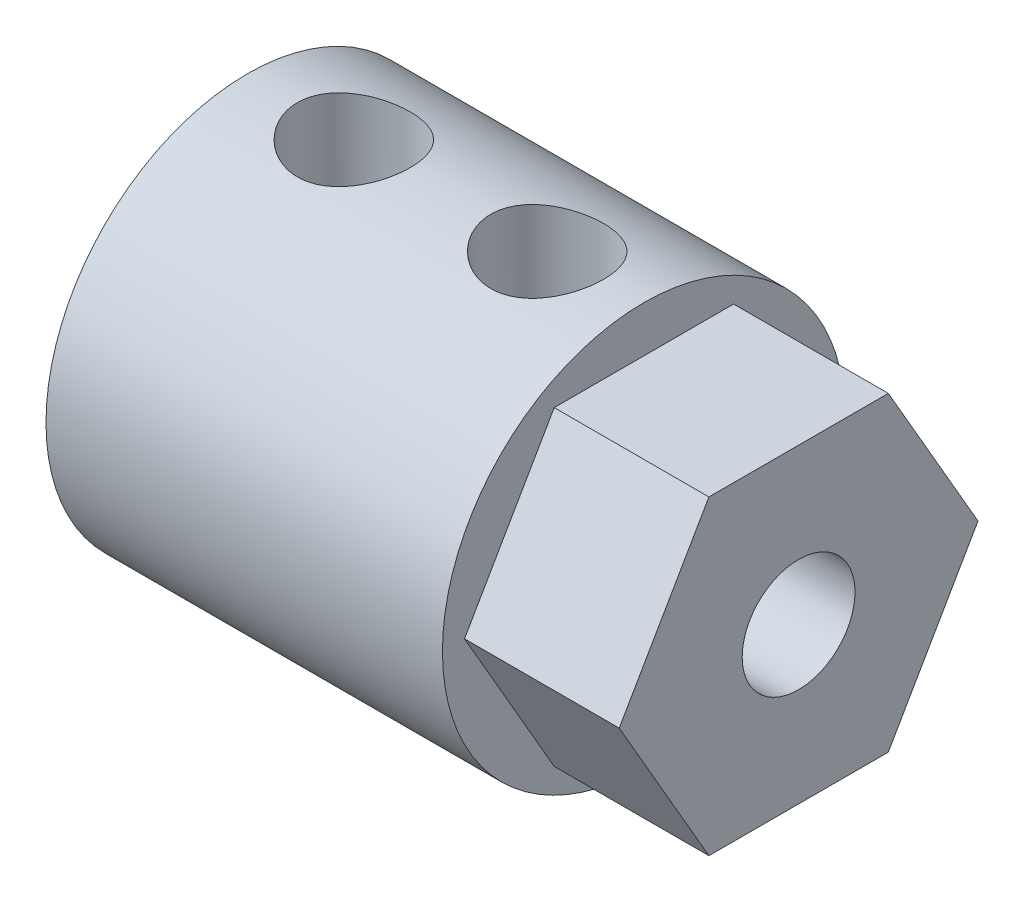
SolidWorks part; units mm, degrees
material "PLA2"
ref_plane "Front Plane" through (0, 0, 0) normal (0, 0, 1) x (1, 0, 0)
ref_plane "Top Plane" through (0, 0, 0) normal (0, 1, 0) x (1, 0, 0)
ref_plane "Right Plane" through (0, 0, 0) normal (1, 0, 0) x (0, 0, -1)
sketch "Sketch1" plane through (0, 0, 0) normal (1, 0, 0) x (0, 0, -1)
  line L0 (0, 0) -> (50000, 0) construction
  line L1 (-3.5342, 6.1214) -> (3.5342, 6.1214)
  line L2 (3.5342, 6.1214) -> (7.0684, 0)
  line L3 (0, 0) -> (0, 50000) construction
  line L4 (-3.5342, 6.1214) -> (-7.0684, 0)
  line L5 (-3.5342, -6.1214) -> (-7.0684, 0)
  line L6 (3.5342, -6.1214) -> (7.0684, 0)
  line L7 (-3.5342, -6.1214) -> (3.5342, -6.1214)
  point P8 (0, 6.1214)
  point P13 (0, -6.1214)
  dimension "D1" = 12.2428
  dimension "D2" = 12.2428
extrude "Hex" add sketch "Sketch1" along normal blind 6.096
sketch "Sketch2" plane through (0, 0, 0) normal (-1, 0, 0) x (0, 0, 1)
  circle A0 centre (0, 0) radius 7.9375
  circle A1 centre (0, 0) radius 3.2639
  dimension "D1" = 6.5278
  dimension "D2" = 15.875
extrude "Rotary_Shaft" add sketch "Sketch2" along normal blind 15.621
fillet "Fillet1" [suppressed] radius 0.889
fillet "Fillet2" [suppressed] radius 0.508
fillet "Fillet3" [suppressed] radius 0.508
sketch "Sketch3" plane through (0, 0, 0) normal (0, 1, 0) x (1, 0, 0)
  line L0 (-15.621, -7.9375) -> (0, -7.9375) construction
  line L1 (-15.621, 7.9375) -> (-15.621, -7.9375) construction
  line L2 (0, 7.9375) -> (-15.621, 7.9375) construction
  line L3 (-15.621, -7.9375) -> (0, -7.9375) construction
  line L4 (-15.621, 7.9375) -> (-15.621, -7.9375) construction
  line L5 (0, 7.9375) -> (-15.621, 7.9375) construction
  line L6 (-15.621, 0) -> (0, 0) construction
  circle A0 centre (-11.43, 0) radius 2.2225
  circle A1 centre (-3.81, 0) radius 2.2225
  dimension "D1" = 4.445
  dimension "D2" = 4.445
  dimension "D3" = 4.191
  dimension "D4" = 7.62
extrude "Shaft-SetScrew-Holes" cut sketch "Sketch3" along normal through all
sketch "Sketch4" plane through (0, 0, 0) normal (-1, 0, 0) x (0, 0, 1)
  circle A0 centre (0, 0) radius 2.2225
  dimension "D1" = 4.445
extrude "Cut-Extrude2" cut sketch "Sketch4" against normal through all
equation "\"D2@Sketch3\"=\"D1@Sketch3\""
equation "\"D2@Sketch1\"=\"D1@Sketch1\""
